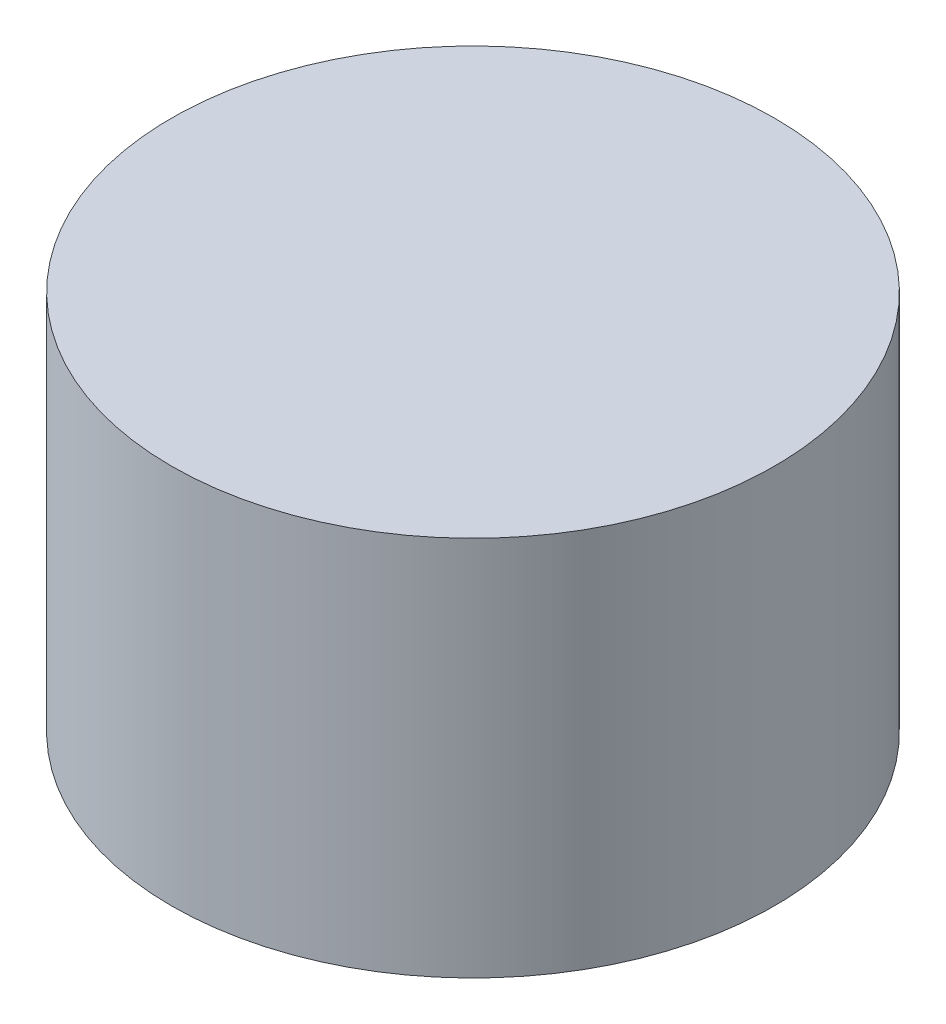
SolidWorks part; units mm, degrees
ref_plane "Front Plane" through (0, 0, 0) normal (0, 0, 1) x (1, 0, 0)
ref_plane "Top Plane" through (0, 0, 0) normal (0, 1, 0) x (1, 0, 0)
ref_plane "Right Plane" through (0, 0, 0) normal (1, 0, 0) x (0, 0, -1)
sketch "Sketch1" plane through (0, 0, 0) normal (0, 1, 0) x (1, 0, 0)
  circle A0 centre (0, 0) radius 4.75
extrude "Boss-Extrude1" add sketch "Sketch1" along normal blind 6 contours A0
